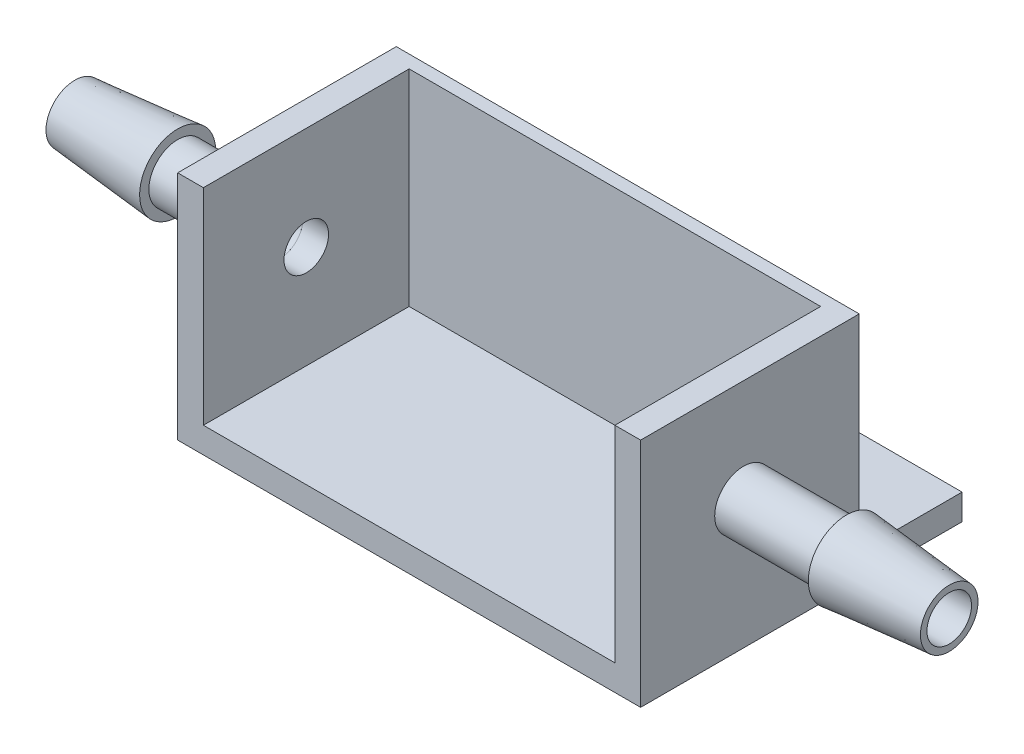
SolidWorks part; units mm, degrees
ref_plane "Front Plane" through (0, 0, 0) normal (0, 0, 1) x (1, 0, 0)
ref_plane "Top Plane" through (0, 0, 0) normal (0, 1, 0) x (1, 0, 0)
ref_plane "Right Plane" through (0, 0, 0) normal (1, 0, 0) x (0, 0, -1)
sketch "Sketch1" plane through (0, 0, 0) normal (0, 0, 1) x (1, 0, 0)
  line L1 (-57.15, 0) -> (57.15, 0)
  line L2 (-57.15, 0) -> (-57.15, 6.35)
  line L3 (-50.8, 6.35) -> (50.8, 6.35)
  line L4 (57.15, 0) -> (57.15, 6.35)
  line L6 (-57.15, 6.35) -> (-57.15, 57.15)
  line L7 (-57.15, 57.15) -> (-50.8, 57.15)
  line L8 (-50.8, 6.35) -> (-50.8, 57.15)
  line L10 (57.15, 6.35) -> (57.15, 57.15)
  line L11 (57.15, 57.15) -> (50.8, 57.15)
  line L12 (50.8, 6.35) -> (50.8, 57.15)
  dimension "D1" = 6.35
  dimension "D2" = 101.6
  dimension "D3" = 6.35
  dimension "D4" = 50.8
extrude "Boss-Extrude1" add sketch "Sketch1" along normal mid plane 50.8
sketch "Sketch2" plane through (0, 0, -25.4) normal (0, 0, -1) x (-1, 0, 0)
  line L0 (57.15, 0) -> (-57.15, 0) construction
  line L1 (-57.15, 57.15) -> (57.15, 57.15)
  line L2 (-57.15, 57.15) -> (-57.15, 0)
  line L3 (-57.15, 0) -> (57.15, 0)
  line L4 (57.15, 57.15) -> (57.15, 0)
extrude "Boss-Extrude2" add sketch "Sketch2" along normal blind 3.175
sketch "Sketch4" plane through (0, 0, 0) normal (0, 0, 1) x (1, 0, 0)
  line L0 (-76.2, 31.75) -> (76.2, 31.75) construction
  line L1 (0, 31.75) -> (0, 0) construction
  line L2 (57.15, 35.687) -> (57.15, 38.862)
  line L3 (-50.8, 6.35) -> (-50.8, 57.15) construction
  line L4 (-57.15, 38.862) -> (-82.55, 38.862)
  line L5 (-57.15, 57.15) -> (-57.15, 0) construction
  line L6 (-82.55, 38.862) -> (-82.55, 41.148)
  line L7 (-82.55, 41.148) -> (-107.95, 38.862)
  line L8 (-107.95, 38.862) -> (-107.95, 35.687)
  line L9 (-107.95, 35.687) -> (-57.15, 35.687) construction
  line L10 (-57.15, 35.687) -> (-57.15, 38.862)
  line L11 (107.95, 35.687) -> (57.15, 35.687)
  line L12 (107.95, 38.862) -> (107.95, 35.687)
  line L13 (82.55, 41.148) -> (107.95, 38.862)
  line L14 (82.55, 38.862) -> (82.55, 41.148)
  line L15 (57.15, 38.862) -> (82.55, 38.862)
  line L16 (-107.95, 35.687) -> (-107.95, 31.75)
  line L17 (-107.95, 31.75) -> (-57.15, 31.75)
  line L18 (-57.15, 31.75) -> (-57.15, 35.687)
  point P3 (-50.8, 31.75)
  dimension "D1" = 7.112
  dimension "D2" = 25.4
  dimension "D3" = 3.175
  dimension "D4" = 25.4
  dimension "D5" = 9.398
revolve "Revolve1" add sketch "Sketch4" angle 360 about L0
sketch "Sketch3" plane through (0, 0, 0) normal (1, 0, 0) x (0, 0, -1)
  line L0 (-25.4, 57.15) -> (28.575, 57.15) construction
  circle A0 centre (0, 31.75) radius 5.5
  dimension "D2" = 11
  dimension "D1" = 25.4
extrude "Cut-Extrude2" cut sketch "Sketch3" against normal through all both and the other way through all
sketch "Sketch5" plane through (0, 0, 0) normal (0, -1, 0) x (-1, 0, 0)
  line L0 (-57.15, -25.4) -> (-57.15, 28.575) construction
  line L1 (57.15, 28.575) -> (-57.15, 28.575)
  line L2 (57.15, 28.575) -> (57.15, 53.975)
  line L3 (57.15, 53.975) -> (-57.15, 53.975)
  line L4 (-57.15, 28.575) -> (-57.15, 53.975)
  circle A0 centre (-38.1, 41.275) radius 3.429
  circle A1 centre (-12.7, 41.275) radius 3.429
  circle A2 centre (12.7, 41.275) radius 3.429
  circle A3 centre (38.1, 41.275) radius 3.429
  point P10 (-57.15, 41.275)
  dimension "D2" = 6.858
  dimension "D1" = 25.4
  dimension "D3" = 19.05
  dimension "D4" = 4
extrude "Boss-Extrude3" add sketch "Sketch5" against normal blind 6.35
